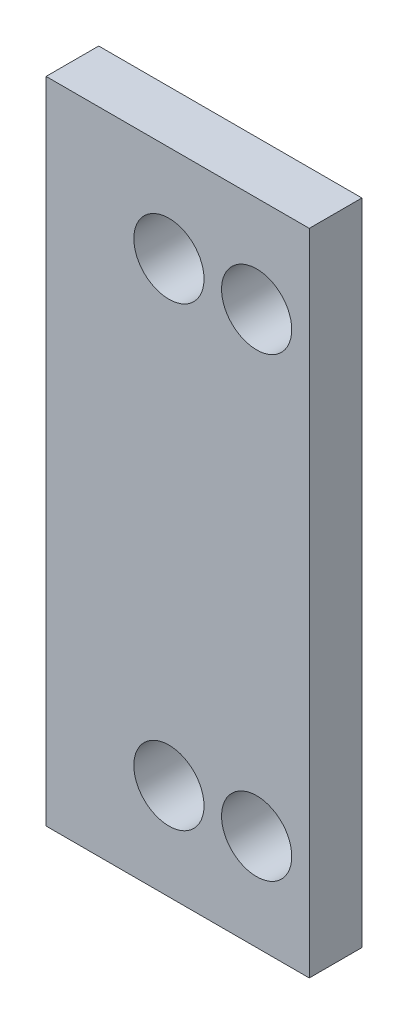
SolidWorks part; units mm, degrees
ref_plane "Plano frontal" through (0, 0, 0) normal (0, 0, 1) x (1, 0, 0)
ref_plane "Plano superior" through (0, 0, 0) normal (0, 1, 0) x (1, 0, 0)
ref_plane "Plano direito" through (0, 0, 0) normal (1, 0, 0) x (0, 0, -1)
sketch "Esboço1" plane through (0, 0, 0) normal (0, 0, 1) x (1, 0, 0)
  line L0 (-6.113, 5.4713) -> (-6.113, 23.9713)
  line L1 (-6.113, 23.9713) -> (1.387, 23.9713)
  line L2 (1.387, 23.9713) -> (8.887, 23.9713)
  line L3 (8.887, 23.9713) -> (8.887, 5.4713)
  line L4 (8.887, 5.4713) -> (8.887, -13.0287)
  line L5 (8.887, -13.0287) -> (1.387, -13.0287)
  line L6 (1.387, -13.0287) -> (-6.113, -13.0287)
  line L7 (-6.113, -13.0287) -> (-6.113, 5.4713)
  line L8 (-6.113, 5.4713) -> (8.887, 5.4713)
  line L9 (5.887, 23.9713) -> (5.887, 18.4713)
  line L10 (5.887, 18.4713) -> (5.887, -7.5287)
  line L11 (5.887, -7.5287) -> (5.887, -13.0287)
  line L12 (5.887, 18.4713) -> (8.887, 18.4713)
  line L13 (5.887, 18.4713) -> (0.887, 18.4713)
  line L14 (5.887, -7.5287) -> (0.887, -7.5287)
  circle A0 centre (0.887, 18.4713) radius 2
  circle A1 centre (5.887, 18.4713) radius 2
  circle A2 centre (0.887, -7.5287) radius 2
  circle A3 centre (5.887, -7.5287) radius 2
other "Alinhar grupo1" parameters "D8"=5.6337, "D9"=4.5898, "D10"=2.7963, "D11"=4.2452, "D12"=4, "D1"=63.3145, "D2"=43.9078, "D3"=29.886, "D4"=7.6981, "D5"=1.3238, "D6"=4.8505, "D7"=4.5, "D13"=0
extrude "Ressalto-extrusão2" add sketch "Esboço1" along normal blind 3 contours L7 L0 L1 L2 L3 L4 L5 L6 | A0 | A1 | A3 | A2
